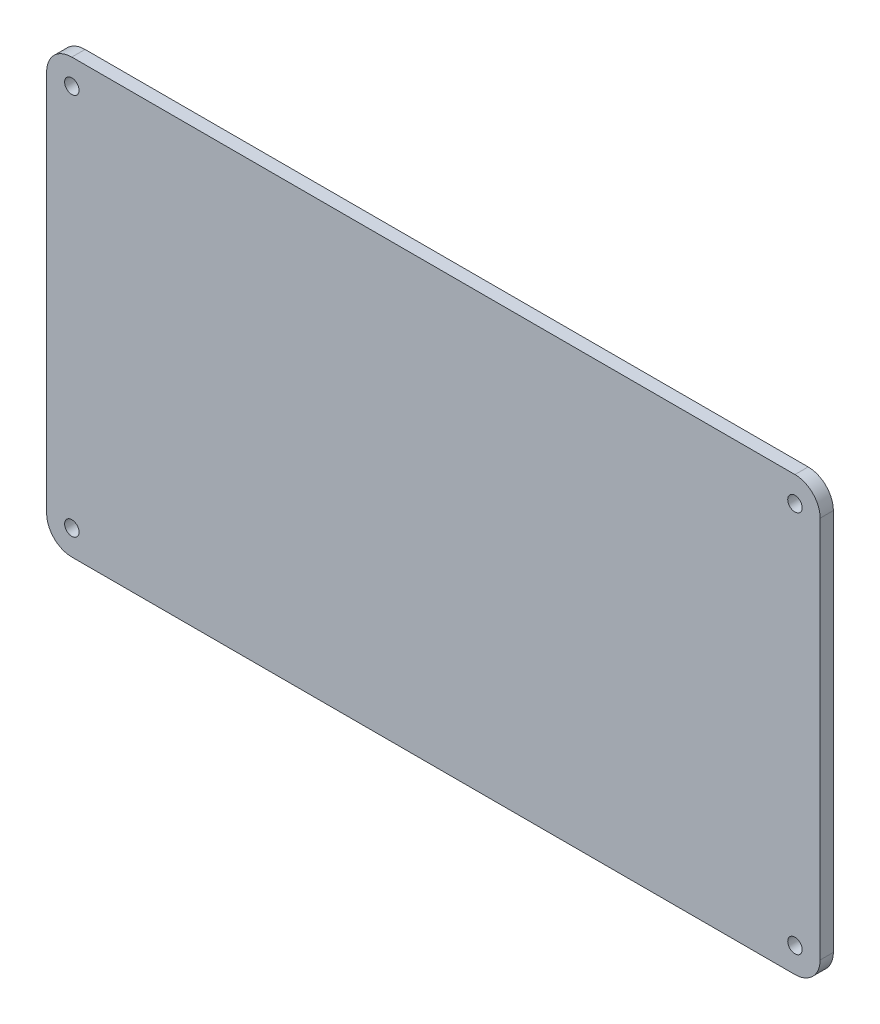
SolidWorks part; units mm, degrees
ref_plane "Front Plane" through (0, 0, 0) normal (0, 0, 1) x (1, 0, 0)
ref_plane "Top Plane" through (0, 0, 0) normal (0, 1, 0) x (1, 0, 0)
ref_plane "Right Plane" through (0, 0, 0) normal (1, 0, 0) x (0, 0, -1)
sketch "Sketch1" plane through (0, 0, 0) normal (0, 0, 1) x (1, 0, 0)
  line L1 (58.5, -32.75) -> (-58.5, -32.75)
  line L2 (58.5, -32.75) -> (58.5, 32.75)
  line L3 (58.5, 32.75) -> (-58.5, 32.75)
  line L4 (-58.5, -32.75) -> (-58.5, 32.75)
  line L5 (0, 32.75) -> (0, -32.75) construction
  line L6 (58.5, 0) -> (-58.5, 0) construction
  point P0 (0, 0)
  dimension "D1" = 117
  dimension "D2" = 65.5
extrude "Boss-Extrude1" add sketch "Sketch1" along normal blind 2
fillet "Fillet1" radius 3.81 1 edges at (-58.5, 32.75, 1)
fillet "Fillet2" radius 3.81 1 edges at (58.5, 32.75, 1)
fillet "Fillet3" radius 3.81 1 edges at (58.5, -32.75, 1)
fillet "Fillet5" radius 3.81 1 edges at (-58.5, -32.75, 1)
sketch "Sketch3" plane through (0, 0, 0) normal (0, 0, -1) x (-1, 0, 0)
  line L0 (-54.69, -32.75) -> (-58.5, -28.94) construction
  line L1 (-58.5, -28.94) -> (-54.69, -28.94) construction
  line L2 (-54.69, -28.94) -> (-57.3841, -31.6341) construction
  arc A0 (-58.5, -28.94) -> (-54.69, -32.75) centre (-54.69, -28.94) ccw construction
  circle A1 centre (-54.69, -28.94) radius 1.0922
  dimension "D1" = 2.1844
extrude "Cut-Extrude1" cut sketch "Sketch3" against normal through all
sketch "Sketch4" plane through (0, 0, 0) normal (0, 0, -1) x (-1, 0, 0)
  line L0 (-54.69, 32.75) -> (-58.5, 28.94) construction
  line L1 (-58.5, 28.94) -> (-57.3841, 31.6341) construction
  line L2 (-57.3841, 31.6341) -> (-54.69, 28.94) construction
  arc A0 (-54.69, 32.75) -> (-58.5, 28.94) centre (-54.69, 28.94) ccw construction
  circle A1 centre (-54.69, 28.94) radius 1.0922
  dimension "D1" = 2.1844
extrude "Cut-Extrude2" cut sketch "Sketch4" against normal through all
sketch "Sketch5" plane through (0, 0, 0) normal (0, 0, -1) x (-1, 0, 0)
  line L0 (57.3841, 31.6341) -> (54.69, 28.94) construction
  arc A0 (58.5, 28.94) -> (54.69, 32.75) centre (54.69, 28.94) ccw construction
  circle A1 centre (54.69, 28.94) radius 1.0922
  dimension "D1" = 2.1844
extrude "Cut-Extrude3" cut sketch "Sketch5" against normal through all
sketch "Sketch6" plane through (0, 0, 0) normal (0, 0, -1) x (-1, 0, 0)
  line L0 (58.5, -28.94) -> (54.69, -32.75) construction
  line L1 (54.69, -32.75) -> (57.3841, -31.6341) construction
  line L2 (57.3841, -31.6341) -> (54.69, -28.94) construction
  arc A0 (54.69, -32.75) -> (58.5, -28.94) centre (54.69, -28.94) ccw construction
  circle A1 centre (54.69, -28.94) radius 1.0922
  dimension "D1" = 2.1844
extrude "Cut-Extrude4" cut sketch "Sketch6" against normal through all
sketch "Sketch7" plane through (0, 0, 0) normal (0, 0, -1) x (-1, 0, 0)
  text T0 "A-TeChToP" font "Comic Sans MS" height in points 42
extrude "Boss-Extrude6" add sketch "Sketch7" along normal blind 1.5
